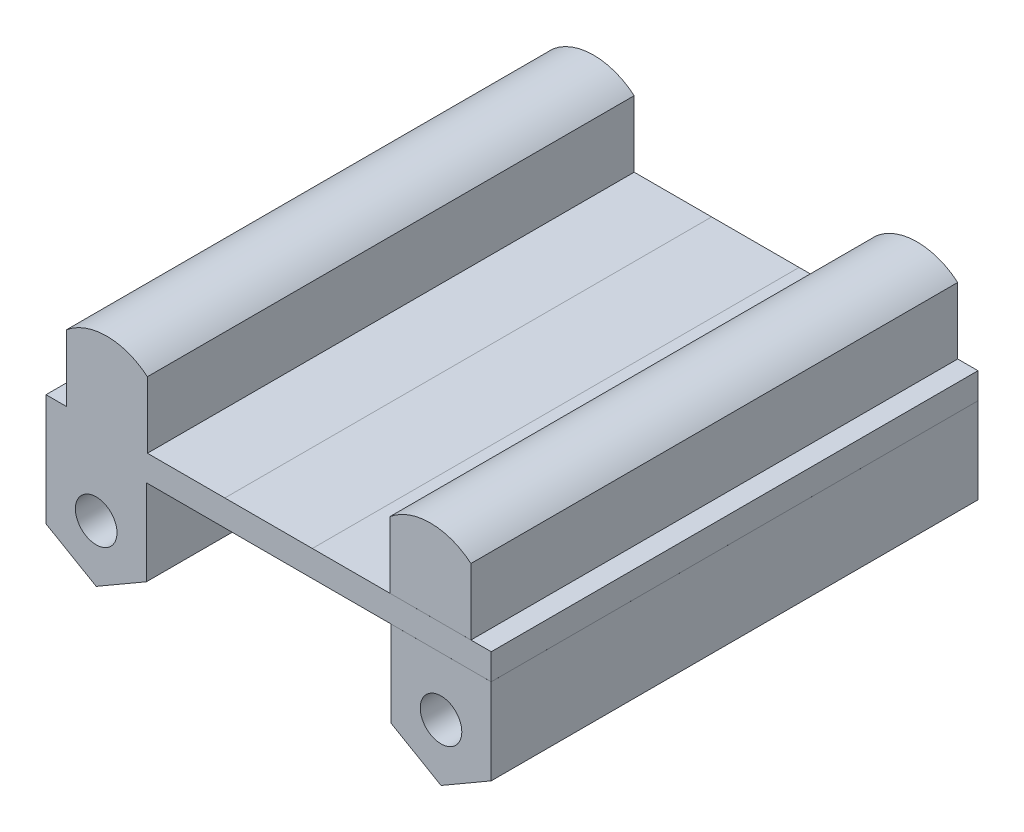
SolidWorks part; units mm, degrees
ref_plane "Front Plane" through (0, 0, 0) normal (0, 0, 1) x (1, 0, 0)
ref_plane "Top Plane" through (0, 0, 0) normal (0, 1, 0) x (1, 0, 0)
ref_plane "Right Plane" through (0, 0, 0) normal (1, 0, 0) x (0, 0, -1)
sketch "Sketch3" plane through (0, 0, 0) normal (0, 0, 1) x (1, 0, 0)
  line L0 (0, 0) -> (4.95, 0)
  line L1 (4.95, 0) -> (4.95, -4.23)
  line L2 (0, 0) -> (0, -4.23)
  line L3 (0, -4.23) -> (2.475, -5.6632)
  line L4 (2.475, -5.6632) -> (4.95, -4.23)
  line L5 (0, 0) -> (10.9749, 0)
  line L6 (14.6231, 0.3758) -> (13.8212, 0.9775)
  line L7 (0, 5) -> (10.975, 5)
  line L18 (17, 0) -> (21.95, 0)
  line L19 (21.95, 0) -> (21.95, -4.23)
  line L20 (17, 0) -> (17, -4.23)
  line L21 (17, -4.23) -> (19.475, -5.6632)
  line L22 (19.475, -5.6632) -> (21.95, -4.23)
  line L23 (13.1316, 1.2844) -> (12.3297, 1.8861)
  line L24 (21.95, 0) -> (21.95, 5)
  line L25 (21.95, 5) -> (10.975, 5)
  line L26 (0, 5) -> (13.7023, 5)
  line L27 (21.9498, -0.0005) -> (10.9749, 0)
  line L28 (0, 0) -> (0, 1.2845)
  line L29 (0, 1.2845) -> (8.8183, 1.2845)
  line L30 (0, 1.2845) -> (0, 0)
  line L31 (21.9498, -0.0005) -> (16.9998, -0.0003)
  line L32 (8.8183, 1.2845) -> (9.6203, 1.8861)
  line L33 (21.9499, 1.284) -> (13.1316, 1.2844)
  line L34 (21.9498, -0.0005) -> (21.9499, 1.284)
  line L35 (10.3099, 0.3759) -> (11.1118, 0.9776)
  arc A1 (12.3297, 1.8861) -> (9.6203, 1.8861) centre (10.975, 2.5301) ccw
  arc A2 (13.8212, 0.9775) -> (11.1118, 0.9776) centre (12.4665, 1.6216) ccw
  dimension "D4" = 3
  dimension "D1" = 4.23
  dimension "D2" = 2.86
  dimension "D3" = 4.23
  dimension "D6" = 5
  dimension "D7" = 2.86
  dimension "D8" = 12.05
  dimension "D9" = 10.975
extrude "Boss-Extrude2" add sketch "Sketch3" along normal blind 24 contours L23 A1 L32 L29 L28 L0 L5 L27 L20 L18 L34 L33 | L3 L4 L1 L0 L2 | L34 L27 L20 L21 L22 L19 L18
sketch "Sketch4" plane through (0, 0, 24) normal (0, 0, 1) x (1, 0, 0)
  line L0 (8.8183, 1.2845) -> (9.6203, 1.8861)
  line L1 (8.8183, 1.2845) -> (9.6203, 1.8861) construction
sketch "Sketch6" plane through (0, 0, 24) normal (0, 0, 1) x (1, 0, 0)
  circle A0 centre (2.475, -2.8632) radius 1.025
  circle A1 centre (19.475, -2.8632) radius 1.025
  dimension "D1" = 2.05
  dimension "D2" = 2.8
  dimension "D3" = 2.05
  dimension "D4" = 2.8
extrude "Cut-Extrude1" cut sketch "Sketch6" against normal blind 5 contours A0 | A1
sketch "Sketch7" plane through (0, 0, 0) normal (0, 0, -1) x (-1, 0, 0)
  line L0 (-2.475, -5.6632) -> (-2.475, -2.8632)
  circle A0 centre (-19.475, -2.8632) radius 1.025
  circle A1 centre (-2.475, -2.8632) radius 1.025
  dimension "D1" = 2.05
  dimension "D2" = 2.8
  dimension "D3" = 2.05
  dimension "D4" = 2.8
extrude "Cut-Extrude2" cut sketch "Sketch7" against normal blind 5
sketch "Sketch8" plane through (0, 0, 5) normal (0, 0, -1) x (-1, 0, 0)
  circle A1 centre (-19.475, -2.8632) radius 0.9
  circle A3 centre (-2.475, -2.8632) radius 0.9
  dimension "D1" = 1.8
  dimension "D2" = 1.8
extrude "Cut-Extrude3" cut sketch "Sketch8" against normal blind 14
sketch "Sketch9" plane through (0, 0, 24) normal (0, 0, 1) x (1, 0, 0)
  line L0 (8.8183, 1.2845) -> (13.1316, 1.2844)
  line L1 (13.1316, 1.2844) -> (13.1316, 4.4319)
  line L2 (13.1316, 4.4319) -> (8.8183, 4.4319)
  line L3 (8.8183, 4.4319) -> (8.8183, 1.2845)
extrude "Cut-Extrude4" cut sketch "Sketch9" against normal blind 24
sketch "Sketch10" plane through (0, 0, 24) normal (0, 0, 1) x (1, 0, 0)
  line L0 (10.9749, 1.2844) -> (10.9749, 6.0351)
  line L1 (8.8183, 1.2845) -> (13.1316, 1.2844) construction
  line L2 (0, 1.2845) -> (8.8183, 1.2845) construction
  line L3 (0.9998, 1.2845) -> (4.9998, 1.2845)
  line L4 (0.9998, 1.2845) -> (0.9998, 4.5518)
  line L6 (4.9998, 1.2845) -> (4.9998, 4.5518)
  line L7 (20.9501, 1.2845) -> (16.9501, 1.2845)
  line L11 (20.9501, 1.2845) -> (20.9501, 4.5518)
  line L12 (20.9501, 1.2845) -> (16.9501, 1.2845)
  line L13 (16.9501, 1.2845) -> (16.9501, 4.5518)
  arc A0 (0.9998, 4.5518) -> (4.9998, 4.5518) centre (2.9998, 2.1884) cw
  arc A1 (20.9501, 4.5518) -> (16.9501, 4.5518) centre (18.9501, 2.1884) ccw
extrude "Boss-Extrude3" add sketch "Sketch10" against normal blind 24
